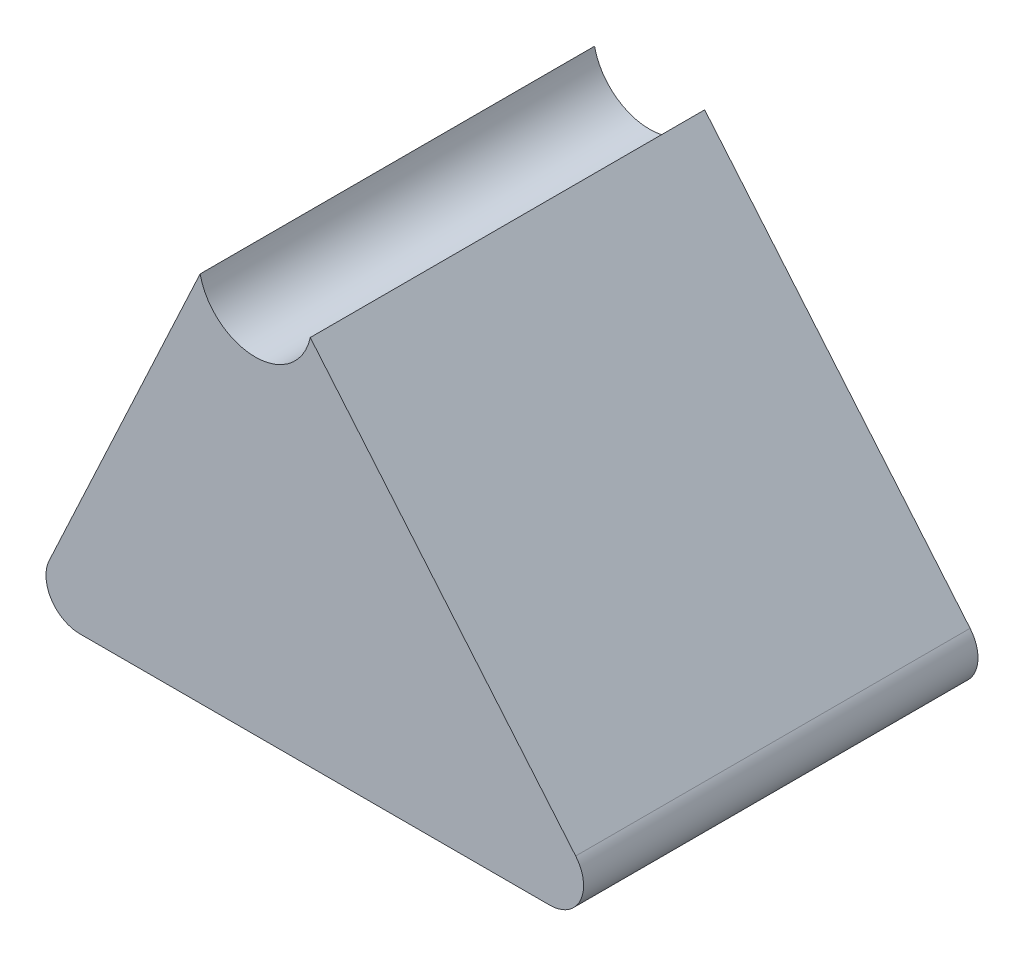
SolidWorks part; units mm, degrees
ref_plane "정면" through (0, 0, 0) normal (0, 0, 1) x (1, 0, 0)
ref_plane "윗면" through (0, 0, 0) normal (0, 1, 0) x (1, 0, 0)
ref_plane "우측면" through (0, 0, 0) normal (1, 0, 0) x (0, 0, -1)
sketch "스케치1" plane through (0, 0, 0) normal (0, 0, 1) x (1, 0, 0)
  line L0 (0, 0) -> (52.8515, 0)
  line L1 (52.8515, 0) -> (25.1612, 33)
  line L2 (0, 0) -> (15.3882, 33)
  arc A0 (25.1612, 33) -> (15.3882, 33) centre (20.2747, 34.0593) cw
  point P6 (45.8959, 45.8959)
  point P7 (73.5631, 45.8959)
  point P8 (0, 0)
  point P9 (21.3014, 34.5598)
  point P10 (21.3014, 34.5598)
  point P11 (26.2819, 34.5598)
  point P12 (21.3014, 35)
  point P13 (0, 0)
  point P14 (26.2251, 35)
  point P15 (20.2747, 34.0593)
  point P18 (19.7929, 34.0351)
  dimension "D1" = 50
  dimension "D3" = 5
  dimension "D2" = 65
  dimension "D4" = 33
  dimension "D5" = 34.0593
extrude "보스-돌출1" add sketch "스케치1" along normal blind 35
fillet "필렛1" radius 3 2 edges at (52.8515, 0, 17.5) (0, 0, 17.5)
